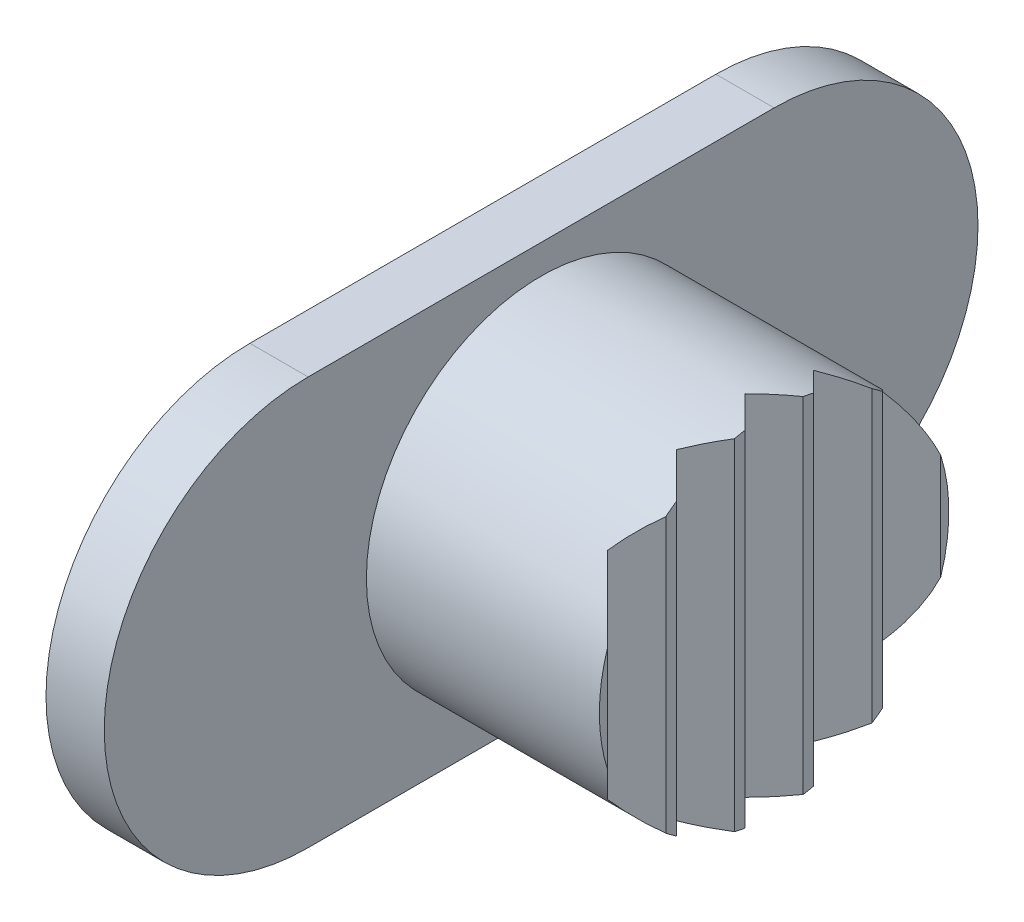
SolidWorks part; units mm, degrees
ref_plane "Front Plane" through (0, 0, 0) normal (0, 0, 1) x (1, 0, 0)
ref_plane "Top Plane" through (0, 0, 0) normal (0, 1, 0) x (1, 0, 0)
ref_plane "Right Plane" through (0, 0, 0) normal (1, 0, 0) x (0, 0, -1)
sketch "Sketch1" plane through (0, 0, 0) normal (1, 0, 0) x (0, 0, -1)
  line L1 (-1.8, -1.8) -> (1.8, -1.8)
  line L2 (-1.8, -1.8) -> (-1.8, 1.8)
  line L3 (-1.8, 1.8) -> (1.8, 1.8)
  line L4 (1.8, -1.8) -> (1.8, 1.8)
  line L5 (-1.8, -1.8) -> (1.8, 1.8) construction
  line L6 (-1.8, 1.8) -> (1.8, -1.8) construction
  circle A0 centre (0, 0) radius 3
  point P0 (0, 0)
  dimension "D3" = 6
  dimension "D1" = 3.6
  dimension "D2" = 3.6
extrude "Boss-Extrude1" add sketch "Sketch1" along normal blind 4
sketch "Sketch2" plane through (0, 0, 0) normal (-1, 0, 0) x (0, 0, 1)
  line L0 (-4, 0) -> (4, 0) construction
  line L1 (-4, 3.5) -> (4, 3.5)
  line L2 (-4, -3.5) -> (4, -3.5)
  line L3 (-1.8, -1.8) -> (-1.8, 1.8) construction
  line L6 (-1.8, 1.8) -> (1.8, 1.8) construction
  line L7 (1.8, 1.8) -> (1.8, -1.8) construction
  line L8 (1.8, -1.8) -> (-1.8, -1.8) construction
  line L9 (-1.8, -1.8) -> (-1.8, 1.8)
  line L10 (-1.8, 1.8) -> (1.8, 1.8)
  line L11 (1.8, 1.8) -> (1.8, -1.8)
  line L12 (1.8, -1.8) -> (-1.8, -1.8)
  arc A0 (-4, 3.5) -> (-4, -3.5) centre (-4, 0) ccw
  arc A1 (4, -3.5) -> (4, 3.5) centre (4, 0) ccw
  point P2 (0, 0)
  dimension "D1" = 3.5
  dimension "D3" = 8
extrude "Boss-Extrude2" add sketch "Sketch2" against normal blind 1
sketch "Sketch3" plane through (4, 0, 0) normal (1, 0, 0) x (0, 0, -1)
  circle A0 centre (0, 0) radius 3 construction
  circle A1 centre (0, 0) radius 3
extrude "Boss-Extrude3" add sketch "Sketch3" along normal blind 1
sketch "Sketch5" plane through (0, 0, 0) normal (0, 1, 0) x (1, 0, 0)
  line L0 (5, -3) -> (5, 3) construction
  line L1 (5, -3) -> (5, 3) construction
  line L2 (5, 2.86) -> (4.5, 2.36)
  line L3 (4.5, 2.36) -> (5, 1.86)
  line L4 (5, 1.86) -> (5, 2.86)
  line L5 (5, 1.68) -> (4.5, 1.18)
  line L6 (4.5, 1.18) -> (5, 0.68)
  line L7 (5, 0.68) -> (5, 1.68)
  line L8 (5, 0.5) -> (4.5, 0)
  line L9 (4.5, 0) -> (5, -0.5)
  line L10 (5, -0.5) -> (5, 0.5)
  line L11 (5, -0.68) -> (4.5, -1.18)
  line L12 (4.5, -1.18) -> (5, -1.68)
  line L13 (5, -1.68) -> (5, -0.68)
  line L14 (5, -1.86) -> (4.5, -2.36)
  line L15 (4.5, -2.36) -> (5, -2.86)
  line L16 (5, -2.86) -> (5, -1.86)
  line L18 (0, 0) -> (4.5, 0) construction
  dimension "D1" = 0.5
  dimension "D3" = 0.18
  dimension "D2" = 5
extrude "Cut-Extrude2" cut sketch "Sketch5" against normal through all both and the other way through all
